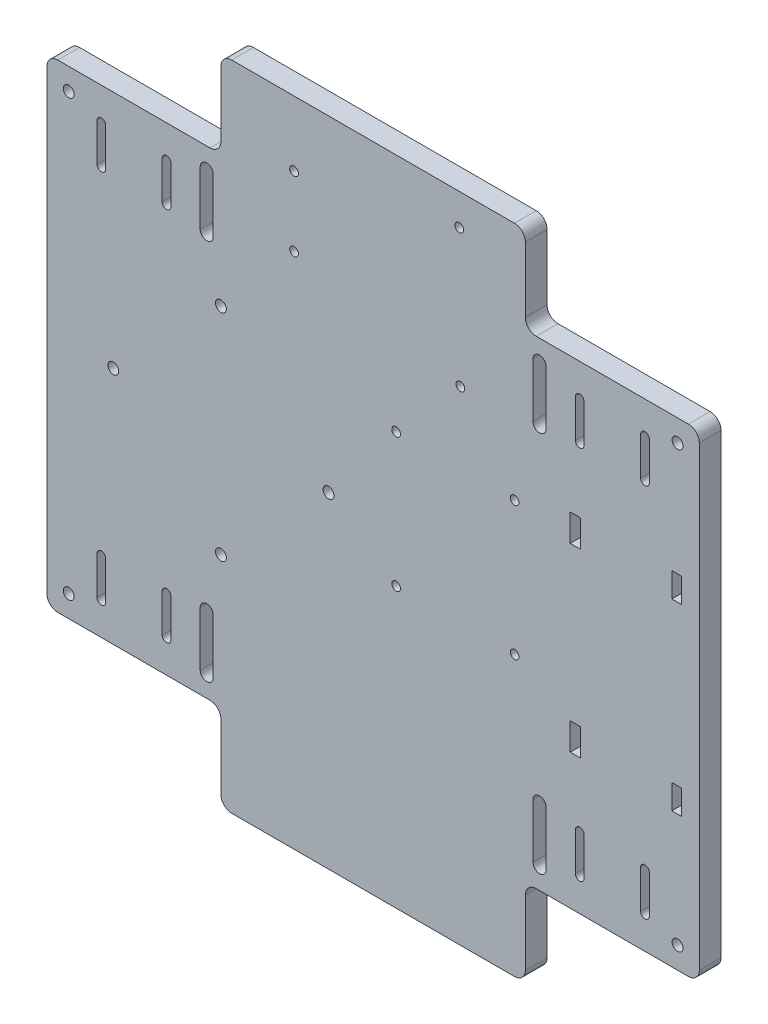
SolidWorks part; units mm, degrees
ref_plane "前视基准面" through (0, 0, 0) normal (0, 0, 1) x (1, 0, 0)
ref_plane "上视基准面" through (0, 0, 0) normal (0, 1, 0) x (1, 0, 0)
ref_plane "右视基准面" through (0, 0, 0) normal (1, 0, 0) x (0, 0, -1)
other "Configuration Table"
sketch "草图1" plane through (0, 0, 0) normal (0, 0, 1) x (1, 0, 0)
  line L0 (-0.0293, 147.9876) -> (299.9707, 147.9876) construction
  line L1 (84.9707, -2.0124) -> (214.9707, -2.0124)
  line L2 (-0.0293, 42.9876) -> (-0.0293, 252.9876)
  line L3 (84.9707, 297.9876) -> (214.9707, 297.9876)
  line L4 (299.9707, 42.9876) -> (299.9707, 252.9876)
  line L7 (4.9707, 37.9876) -> (74.9707, 37.9876)
  line L8 (79.9707, 2.9876) -> (79.9707, 32.9876)
  line L9 (149.9707, 297.9876) -> (149.9707, -2.0124) construction
  line L10 (4.9707, 257.9876) -> (74.9707, 257.9876)
  line L11 (79.9707, 292.9876) -> (79.9707, 262.9876)
  line L14 (294.9707, 37.9876) -> (224.9707, 37.9876)
  line L15 (219.9707, 2.9876) -> (219.9707, 32.9876)
  line L19 (219.9707, 292.9876) -> (219.9707, 262.9876)
  line L20 (294.9707, 257.9876) -> (224.9707, 257.9876)
  line L22 (24.9707, 242.9876) -> (54.9707, 242.9876) construction
  line L23 (24.9707, 242.9876) -> (24.9707, 225.4876) construction
  line L24 (24.9707, 225.4876) -> (54.9707, 225.4876) construction
  line L25 (54.9707, 242.9876) -> (54.9707, 225.4876) construction
  line L26 (244.9707, 242.9876) -> (244.9707, 225.4876) construction
  line L27 (274.9707, 242.9876) -> (244.9707, 242.9876) construction
  line L28 (274.9707, 242.9876) -> (274.9707, 225.4876) construction
  line L29 (274.9707, 225.4876) -> (244.9707, 225.4876) construction
  line L30 (274.9707, 52.9876) -> (244.9707, 52.9876) construction
  line L31 (244.9707, 52.9876) -> (244.9707, 70.4876) construction
  line L32 (274.9707, 70.4876) -> (244.9707, 70.4876) construction
  line L33 (274.9707, 52.9876) -> (274.9707, 70.4876) construction
  line L34 (54.9707, 52.9876) -> (54.9707, 70.4876) construction
  line L35 (24.9707, 52.9876) -> (54.9707, 52.9876) construction
  line L36 (24.9707, 52.9876) -> (24.9707, 70.4876) construction
  line L37 (79.9707, 297.9876) -> (79.9707, 262.9876)
  line L38 (-0.0293, 257.9876) -> (74.9707, 257.9876)
  line L39 (-0.0293, 37.9876) -> (74.9707, 37.9876)
  line L40 (79.9707, -2.0124) -> (79.9707, 32.9876)
  line L41 (79.9707, -2.0124) -> (219.9707, -2.0124)
  line L42 (219.9707, -2.0124) -> (219.9707, 32.9876)
  line L43 (299.9707, 37.9876) -> (224.9707, 37.9876)
  line L44 (299.9707, 257.9876) -> (224.9707, 257.9876)
  line L45 (219.9707, 297.9876) -> (219.9707, 262.9876)
  line L46 (79.9707, 297.9876) -> (219.9707, 297.9876)
  line L47 (24.9707, 70.4876) -> (54.9707, 70.4876) construction
  line L48 (234.9707, 204.4876) -> (284.9707, 204.4876) construction
  line L49 (234.9707, 37.9876) -> (284.9707, 37.9876) construction
  line L50 (234.9707, 37.9876) -> (234.9707, 91.4876) construction
  line L51 (234.9707, 91.4876) -> (284.9707, 91.4876) construction
  line L52 (284.9707, 37.9876) -> (284.9707, 91.4876) construction
  line L53 (284.9707, 257.9876) -> (284.9707, 204.4876) construction
  line L54 (234.9707, 257.9876) -> (284.9707, 257.9876) construction
  line L55 (234.9707, 257.9876) -> (234.9707, 204.4876) construction
  line L56 (64.9707, 91.4876) -> (14.9707, 91.4876) construction
  line L57 (14.9707, 37.9876) -> (14.9707, 91.4876) construction
  line L58 (64.9707, 37.9876) -> (14.9707, 37.9876) construction
  line L59 (64.9707, 37.9876) -> (64.9707, 91.4876) construction
  line L60 (64.9707, 257.9876) -> (64.9707, 204.4876) construction
  line L61 (64.9707, 257.9876) -> (14.9707, 257.9876) construction
  line L62 (14.9707, 257.9876) -> (14.9707, 204.4876) construction
  line L63 (64.9707, 204.4876) -> (14.9707, 204.4876) construction
  line L64 (287.3162, 100.1548) -> (291.8708, 100.1548)
  line L65 (245.3162, 222.9876) -> (287.3162, 222.9876) construction
  line L66 (245.3162, 222.9876) -> (245.3162, 72.9876) construction
  line L67 (245.3162, 72.9876) -> (287.3162, 72.9876) construction
  line L68 (287.3162, 222.9876) -> (287.3162, 72.9876) construction
  line L69 (245.3162, 195.8204) -> (240.5982, 195.8204)
  line L70 (245.3162, 195.8204) -> (245.3162, 183.3094)
  line L71 (245.3162, 183.3094) -> (240.5982, 183.3094)
  line L72 (240.5982, 195.8204) -> (240.5982, 183.3094)
  line L73 (287.3162, 184.5393) -> (291.8708, 184.5393)
  line L74 (287.3162, 184.5393) -> (287.3162, 195.8204)
  line L75 (287.3162, 195.8204) -> (291.8708, 195.8204)
  line L76 (291.8708, 184.5393) -> (291.8708, 195.8204)
  line L77 (291.8708, 111.4358) -> (291.8708, 100.1548)
  line L78 (287.3162, 111.4358) -> (291.8708, 111.4358)
  line L79 (287.3162, 111.4358) -> (287.3162, 100.1548)
  line L80 (245.3162, 112.6658) -> (240.5982, 112.6658)
  line L81 (240.5982, 100.1548) -> (240.5982, 112.6658)
  line L82 (245.3162, 100.1548) -> (240.5982, 100.1548)
  line L83 (245.3162, 100.1548) -> (245.3162, 112.6658)
  line L84 (194.1063, 224.0826) -> (202.6063, 224.0826) construction
  line L85 (117.6063, 280.0826) -> (185.6063, 280.0826) construction
  line L86 (117.6063, 280.0826) -> (117.6063, 272.0826) construction
  line L87 (117.6063, 224.0826) -> (185.6063, 224.0826) construction
  line L88 (202.6063, 280.0826) -> (202.6063, 224.0826) construction
  line L90 (185.6063, 280.0826) -> (185.6063, 287.5826) construction
  line L91 (185.6063, 287.5826) -> (194.1063, 287.5826) construction
  line L92 (194.1063, 280.0826) -> (194.1063, 287.5826) construction
  line L94 (194.1063, 224.0826) -> (194.1063, 216.5826) construction
  line L95 (194.1063, 216.5826) -> (185.6063, 216.5826) construction
  line L96 (185.6063, 224.0826) -> (185.6063, 216.5826) construction
  line L97 (117.6063, 272.0826) -> (109.6063, 272.0826) construction
  line L99 (117.6063, 264.0826) -> (109.6063, 264.0826) construction
  line L100 (109.6063, 272.0826) -> (109.6063, 264.0826) construction
  line L101 (117.6063, 240.0826) -> (109.6063, 240.0826) construction
  line L103 (117.6063, 232.0826) -> (109.6063, 232.0826) construction
  line L104 (109.6063, 240.0826) -> (109.6063, 232.0826) construction
  line L105 (194.1063, 280.0826) -> (202.6063, 280.0826) construction
  line L106 (117.6063, 264.0826) -> (117.6063, 240.0826) construction
  line L107 (117.6063, 232.0826) -> (117.6063, 224.0826) construction
  line L108 (24.9707, 70.4876) -> (24.9707, 52.9876) construction
  line L109 (157.7933, 191.5114) -> (217.7933, 191.5114) construction
  line L110 (157.7933, 191.5114) -> (157.7933, 122.5114) construction
  line L111 (157.7933, 122.5114) -> (217.7933, 122.5114) construction
  line L112 (217.7933, 191.5114) -> (217.7933, 122.5114) construction
  line L113 (26.9707, 70.4876) -> (26.9707, 52.9876)
  line L114 (22.9707, 70.4876) -> (22.9707, 52.9876)
  line L115 (54.9707, 70.4876) -> (54.9707, 52.9876) construction
  line L116 (56.9707, 70.4876) -> (56.9707, 52.9876)
  line L117 (52.9707, 70.4876) -> (52.9707, 52.9876)
  line L118 (244.9707, 70.4876) -> (244.9707, 52.9876) construction
  line L119 (246.9707, 70.4876) -> (246.9707, 52.9876)
  line L120 (242.9707, 70.4876) -> (242.9707, 52.9876)
  line L121 (274.9707, 52.9876) -> (274.9707, 70.4876) construction
  line L122 (272.9707, 52.9876) -> (272.9707, 70.4876)
  line L123 (276.9707, 52.9876) -> (276.9707, 70.4876)
  line L124 (24.9707, 225.4876) -> (24.9707, 242.9876) construction
  line L125 (26.9707, 225.4876) -> (26.9707, 242.9876)
  line L126 (22.9707, 225.4876) -> (22.9707, 242.9876)
  line L127 (54.9707, 225.4876) -> (54.9707, 242.9876) construction
  line L128 (56.9707, 225.4876) -> (56.9707, 242.9876)
  line L129 (52.9707, 225.4876) -> (52.9707, 242.9876)
  line L130 (244.9707, 225.4876) -> (244.9707, 242.9876) construction
  line L131 (246.9707, 225.4876) -> (246.9707, 242.9876)
  line L132 (242.9707, 225.4876) -> (242.9707, 242.9876)
  line L133 (274.9707, 242.9876) -> (274.9707, 225.4876) construction
  line L134 (272.9707, 242.9876) -> (272.9707, 225.4876)
  line L135 (276.9707, 242.9876) -> (276.9707, 225.4876)
  line L136 (157.7933, 157.0114) -> (217.7933, 157.0114) construction
  line L137 (226.4945, 248.2611) -> (226.4945, 223.2611) construction
  line L140 (229.4945, 248.2611) -> (229.4945, 223.2611)
  line L143 (223.4945, 248.2611) -> (223.4945, 223.2611)
  line L146 (73.4468, 248.2611) -> (73.4468, 223.2611) construction
  line L149 (70.4468, 248.2611) -> (70.4468, 223.2611)
  line L150 (76.4468, 248.2611) -> (76.4468, 223.2611)
  line L151 (73.4468, 47.7141) -> (73.4468, 72.7141) construction
  line L152 (70.4468, 47.7141) -> (70.4468, 72.7141)
  line L153 (76.4468, 47.7141) -> (76.4468, 72.7141)
  line L154 (226.4945, 47.7141) -> (226.4945, 72.7141) construction
  line L155 (229.4945, 47.7141) -> (229.4945, 72.7141)
  line L156 (223.4945, 47.7141) -> (223.4945, 72.7141)
  circle A0 centre (79.9707, 147.9876) radius 60 construction
  circle A1 centre (79.9707, 147.9876) radius 49.5 construction
  circle A2 centre (129.4707, 147.9876) radius 2.5
  circle A3 centre (79.9707, 98.4876) radius 2.5
  circle A4 centre (30.4707, 147.9876) radius 2.5
  circle A5 centre (79.9707, 197.4876) radius 2.5
  circle A22 centre (9.9707, 247.9876) radius 2.5
  circle A24 centre (289.9707, 47.9876) radius 2.5
  circle A25 centre (9.9707, 47.9876) radius 2.5
  circle A26 centre (113.6063, 268.0826) radius 2
  circle A27 centre (113.6063, 236.0826) radius 2
  circle A28 centre (190.1063, 220.5826) radius 2
  circle A29 centre (189.6063, 283.5826) radius 2
  circle A32 centre (215.0333, 187.7214) radius 2
  circle A33 centre (160.5533, 187.7214) radius 2
  circle A34 centre (289.9707, 247.9876) radius 2.5
  arc A35 (26.9707, 70.4876) -> (22.9707, 70.4876) centre (24.9707, 70.4876) ccw
  arc A36 (22.9707, 52.9876) -> (26.9707, 52.9876) centre (24.9707, 52.9876) ccw
  arc A37 (56.9707, 70.4876) -> (52.9707, 70.4876) centre (54.9707, 70.4876) ccw
  arc A38 (52.9707, 52.9876) -> (56.9707, 52.9876) centre (54.9707, 52.9876) ccw
  arc A39 (246.9707, 70.4876) -> (242.9707, 70.4876) centre (244.9707, 70.4876) ccw
  arc A40 (242.9707, 52.9876) -> (246.9707, 52.9876) centre (244.9707, 52.9876) ccw
  arc A41 (272.9707, 52.9876) -> (276.9707, 52.9876) centre (274.9707, 52.9876) ccw
  arc A42 (276.9707, 70.4876) -> (272.9707, 70.4876) centre (274.9707, 70.4876) ccw
  arc A43 (26.9707, 225.4876) -> (22.9707, 225.4876) centre (24.9707, 225.4876) cw
  arc A44 (22.9707, 242.9876) -> (26.9707, 242.9876) centre (24.9707, 242.9876) cw
  arc A45 (56.9707, 225.4876) -> (52.9707, 225.4876) centre (54.9707, 225.4876) cw
  arc A46 (52.9707, 242.9876) -> (56.9707, 242.9876) centre (54.9707, 242.9876) cw
  arc A47 (246.9707, 225.4876) -> (242.9707, 225.4876) centre (244.9707, 225.4876) cw
  arc A48 (242.9707, 242.9876) -> (246.9707, 242.9876) centre (244.9707, 242.9876) cw
  arc A49 (272.9707, 242.9876) -> (276.9707, 242.9876) centre (274.9707, 242.9876) cw
  arc A50 (276.9707, 225.4876) -> (272.9707, 225.4876) centre (274.9707, 225.4876) cw
  circle A51 centre (215.0333, 126.3014) radius 2
  circle A52 centre (160.5533, 126.3014) radius 2
  arc A53 (4.9707, 257.9876) -> (-0.0293, 252.9876) centre (4.9707, 252.9876) ccw
  arc A54 (74.9707, 37.9876) -> (79.9707, 32.9876) centre (74.9707, 32.9876) cw
  arc A55 (-0.0293, 42.9876) -> (4.9707, 37.9876) centre (4.9707, 42.9876) ccw
  arc A56 (84.9707, -2.0124) -> (79.9707, 2.9876) centre (84.9707, 2.9876) cw
  arc A57 (219.9707, 2.9876) -> (214.9707, -2.0124) centre (214.9707, 2.9876) cw
  arc A58 (224.9707, 37.9876) -> (219.9707, 32.9876) centre (224.9707, 32.9876) ccw
  arc A59 (294.9707, 37.9876) -> (299.9707, 42.9876) centre (294.9707, 42.9876) ccw
  arc A60 (294.9707, 257.9876) -> (299.9707, 252.9876) centre (294.9707, 252.9876) cw
  arc A61 (219.9707, 262.9876) -> (224.9707, 257.9876) centre (224.9707, 262.9876) ccw
  arc A62 (214.9707, 297.9876) -> (219.9707, 292.9876) centre (214.9707, 292.9876) cw
  arc A63 (79.9707, 292.9876) -> (84.9707, 297.9876) centre (84.9707, 292.9876) cw
  arc A72 (229.4945, 248.2611) -> (223.4945, 248.2611) centre (226.4945, 248.2611) ccw
  arc A73 (223.4945, 223.2611) -> (229.4945, 223.2611) centre (226.4945, 223.2611) ccw
  arc A74 (70.4468, 248.2611) -> (76.4468, 248.2611) centre (73.4468, 248.2611) cw
  arc A75 (76.4468, 223.2611) -> (70.4468, 223.2611) centre (73.4468, 223.2611) cw
  arc A76 (70.4468, 47.7141) -> (76.4468, 47.7141) centre (73.4468, 47.7141) ccw
  arc A77 (76.4468, 72.7141) -> (70.4468, 72.7141) centre (73.4468, 72.7141) ccw
  arc A78 (229.4945, 47.7141) -> (223.4945, 47.7141) centre (226.4945, 47.7141) cw
  arc A79 (223.4945, 72.7141) -> (229.4945, 72.7141) centre (226.4945, 72.7141) cw
  arc A80 (74.9707, 257.9876) -> (79.9707, 262.9876) centre (74.9707, 262.9876) ccw
  point P44 (244.9707, 61.7376)
  point P55 (24.9707, 61.7376)
  point P144 (54.9707, 61.7376)
  point P150 (274.9707, 61.7376)
  point P155 (24.9707, 234.2376)
  point P160 (54.9707, 234.2376)
  point P165 (244.9707, 234.2376)
  point P170 (274.9707, 234.2376)
  point P204 (226.4945, 235.7611)
  point P211 (73.4468, 235.7611)
  point P218 (73.4468, 60.2141)
  point P225 (226.4945, 60.2141)
  dimension "D1" = 120
  dimension "D2" = 80
  dimension "D5" = 99
  dimension "D6" = 5
  dimension "D7" = 4
  dimension "D11" = 2.76
  dimension "D12" = 54.48
  dimension "D13" = 5
  dimension "D14" = 25
  dimension "D25" = 5
  dimension "D42" = 4
  dimension "D43" = 4
  dimension "D44" = 4
  dimension "D45" = 4
  dimension "D56" = 4
  dimension "D57" = 4
  dimension "D58" = 3
  dimension "D59" = 300
  dimension "D68" = 5
  dimension "D69" = 5
  dimension "D70" = 2
  dimension "D71" = 2
  dimension "D72" = 2
  dimension "D73" = 2
  dimension "D60" = 5
  dimension "D22" = 2
  dimension "D8" = 17.5
  dimension "D9" = 15
  dimension "D10" = 25
  dimension "D15" = 50
  dimension "D16" = 53.5
  dimension "D17" = 15
  dimension "D18" = 30
  dimension "D19" = 30
  dimension "D20" = 150
  dimension "D21" = 42
  dimension "D23" = 220
  dimension "D24" = 75
  dimension "D26" = 10
  dimension "D27" = 10
  dimension "D28" = 56
  dimension "D29" = 85
  dimension "D30" = 7.5
  dimension "D31" = 8.5
  dimension "D32" = 8.5
  dimension "D33" = 7.5
  dimension "D34" = 8.5
  dimension "D35" = 8.5
  dimension "D36" = 24
  dimension "D37" = 8
  dimension "D38" = 8
  dimension "D39" = 8
  dimension "D40" = 8
  dimension "D41" = 8
  dimension "D46" = 4
  dimension "D47" = 4
  dimension "D48" = 4
  dimension "D49" = 4
  dimension "D50" = 4
  dimension "D51" = 4
  dimension "D52" = 4
  dimension "D53" = 4
  dimension "D54" = 60
  dimension "D55" = 69
  dimension "D64" = 3.79
  dimension "D66" = 3.79
  dimension "D67" = 2.76
extrude "凸台-拉伸1" add sketch "草图1" along normal blind 10
